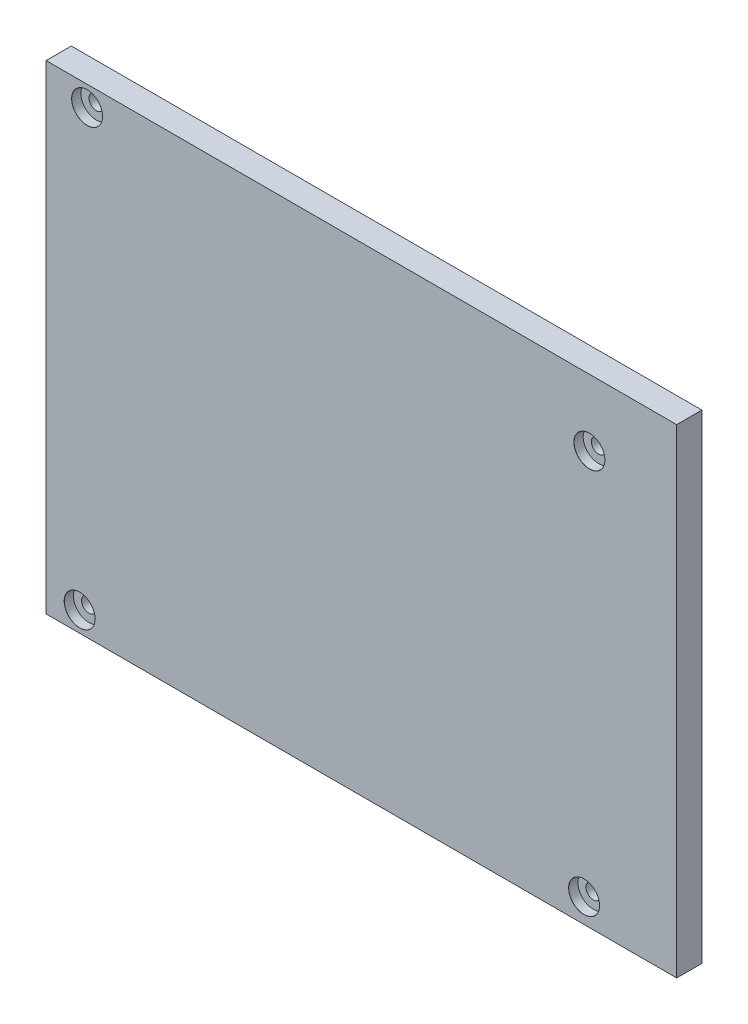
SolidWorks part; units mm, degrees
ref_plane "Front Plane" through (0, 0, 0) normal (0, 0, 1) x (1, 0, 0)
ref_plane "Top Plane" through (0, 0, 0) normal (0, 1, 0) x (1, 0, 0)
ref_plane "Right Plane" through (0, 0, 0) normal (1, 0, 0) x (0, 0, -1)
sketch "Sketch1" plane through (0, 0, 0) normal (0, 0, 1) x (1, 0, 0)
  line L0 (125, -86.5479) -> (125, 103.4521) construction
  line L1 (-125, -86.5479) -> (125, -86.5479)
  line L2 (-125, -86.5479) -> (-125, 103.4521)
  line L3 (-125, 103.4521) -> (125, 103.4521)
  line L4 (125, -86.5479) -> (125, 103.4521)
  point P0 (0, 0)
  dimension "D1" = 190
extrude "Boss-Extrude1" add sketch "Sketch1" along normal blind 10
hole_wizard "CBORE for M5 Hex Head Cap Screw1" positions "Sketch9" profile "Sketch10" counterbore size "M5" standard "ANSI Metric" end condition through all
sketch "Sketch9" plane through (0, 0, 10) normal (0, 0, 1) x (1, 0, 0)
  line L0 (-125, -86.5479) -> (125, -86.5479) construction
  line L2 (125, 103.4521) -> (-125, 103.4521) construction
  point P0 (-108.7491, 95.4521)
  point P2 (-111.7003, -78.5479)
  point P4 (88.2937, -77)
  point P6 (90.4051, 77.078)
  dimension "D1" = 200
  dimension "D2" = 8
  dimension "D3" = 200
  dimension "D4" = 8
sketch "Sketch10" plane through (-108.7491, 95.4521, 10) normal (1, 0, 0) x (0, -1, 0)
  line L0 (0, 0) -> (0, 10)
  line L1 (0, 10) -> (2.9, 10)
  line L3 (2.9, 10) -> (2.9, 3.65)
  line L4 (6.12, 3.65) -> (2.9, 3.65)
  line L5 (6.12, 3.65) -> (6.12, 0.025)
  line L6 (6.12, 0.025) -> (6.145, 0)
  line L7 (6.145, 0) -> (0, 0)
  line L8 (-6.12, 0.025) -> (-6.145, 0) construction
  line L11 (0, -6.35) -> (0, 107.95) construction
  dimension "Thru Hole Dia." = 5.8
  dimension "Thru Hole Depth" = 10
  dimension "C'Bore Dia." = 12.24
  dimension "C'Bore Depth" = 3.65
  dimension "Near C'Sink Dia." = 12.29
  dimension "Near C'Sink Angle" = 90
